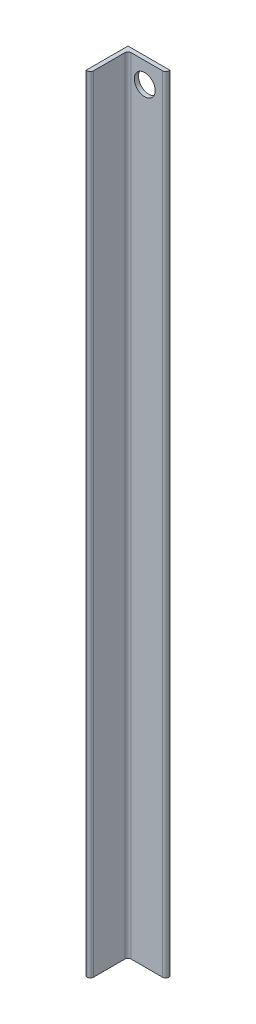
SolidWorks part; units mm, degrees
material "ASTM A36 Steel"
ref_plane "Front Plane" through (0, 0, 0) normal (0, 0, 1) x (1, 0, 0)
ref_plane "Top Plane" through (0, 0, 0) normal (0, 1, 0) x (1, 0, 0)
ref_plane "Right Plane" through (0, 0, 0) normal (1, 0, 0) x (0, 0, -1)
sketch "Sketch1" plane through (0, 0, 0) normal (0, 1, 0) x (1, 0, 0)
  line L0 (-27.4999, 29.2132) -> (-67.4999, 29.2132)
  line L1 (-67.4999, 29.2132) -> (-67.4999, -10.7868)
  line L2 (-67.4999, -10.7868) -> (-66.4999, -10.7868)
  line L3 (-63.4999, -7.7868) -> (-63.4999, 22.2132)
  line L4 (-60.4999, 25.2132) -> (-30.4999, 25.2132)
  line L5 (-27.4999, 28.2132) -> (-27.4999, 29.2132)
  arc A0 (-66.4999, -10.7868) -> (-63.4999, -7.7868) centre (-66.4999, -7.7868) ccw
  arc A1 (-63.4999, 22.2132) -> (-60.4999, 25.2132) centre (-60.4999, 22.2132) cw
  arc A2 (-30.4999, 25.2132) -> (-27.4999, 28.2132) centre (-30.4999, 28.2132) ccw
  point P8 (-63.4999, -10.7868)
  point P13 (-27.4999, 25.2132)
  dimension "D5" = 3
  dimension "D1" = 40
  dimension "D2" = 40
  dimension "D3" = 4
  dimension "D4" = 4
extrude "Boss-Extrude1" add sketch "Sketch1" along normal blind 750
sketch "Sketch2" plane through (0, 0, -25.2132) normal (0, 0, 1) x (1, 0, 0)
  line L0 (-27.4999, 750) -> (-27.4999, 0) construction
  line L1 (-60.4999, 750) -> (-30.4999, 750) construction
  circle A0 centre (-47.4999, 730) radius 10
  dimension "D1" = 20
  dimension "D2" = 20
  dimension "D3" = 20
extrude "Cut-Extrude1" cut sketch "Sketch2" against normal through all
